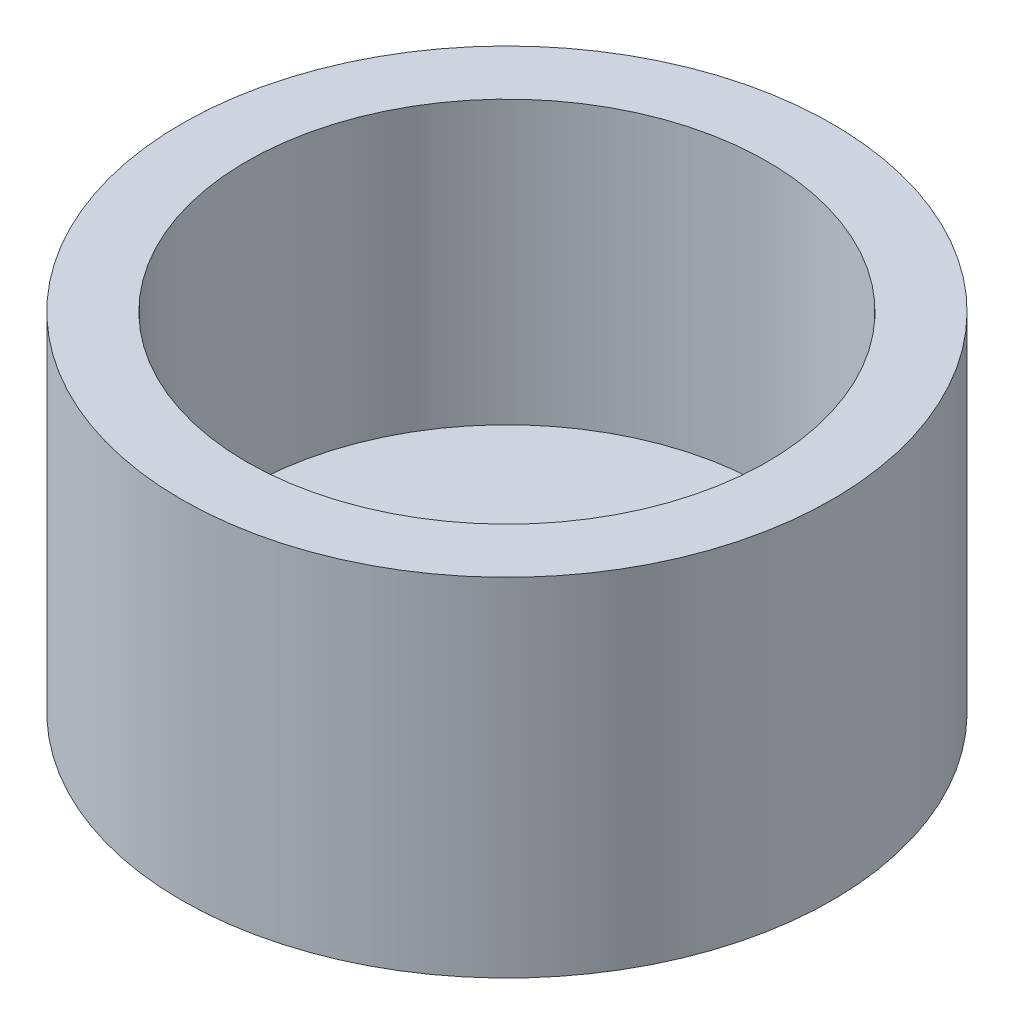
SolidWorks part; units mm, degrees
material "ABS"
ref_plane "Front Plane" through (0, 0, 0) normal (0, 0, 1) x (1, 0, 0)
ref_plane "Top Plane" through (0, 0, 0) normal (0, 1, 0) x (1, 0, 0)
ref_plane "Right Plane" through (0, 0, 0) normal (1, 0, 0) x (0, 0, -1)
sketch "Sketch1" plane through (0, 0, 0) normal (0, 1, 0) x (1, 0, 0)
  circle A0 centre (0, 0) radius 75
  dimension "D1" = 150
extrude "Boss-Extrude1" add sketch "Sketch1" along normal blind 80
shell "Shell4" thickness 15
